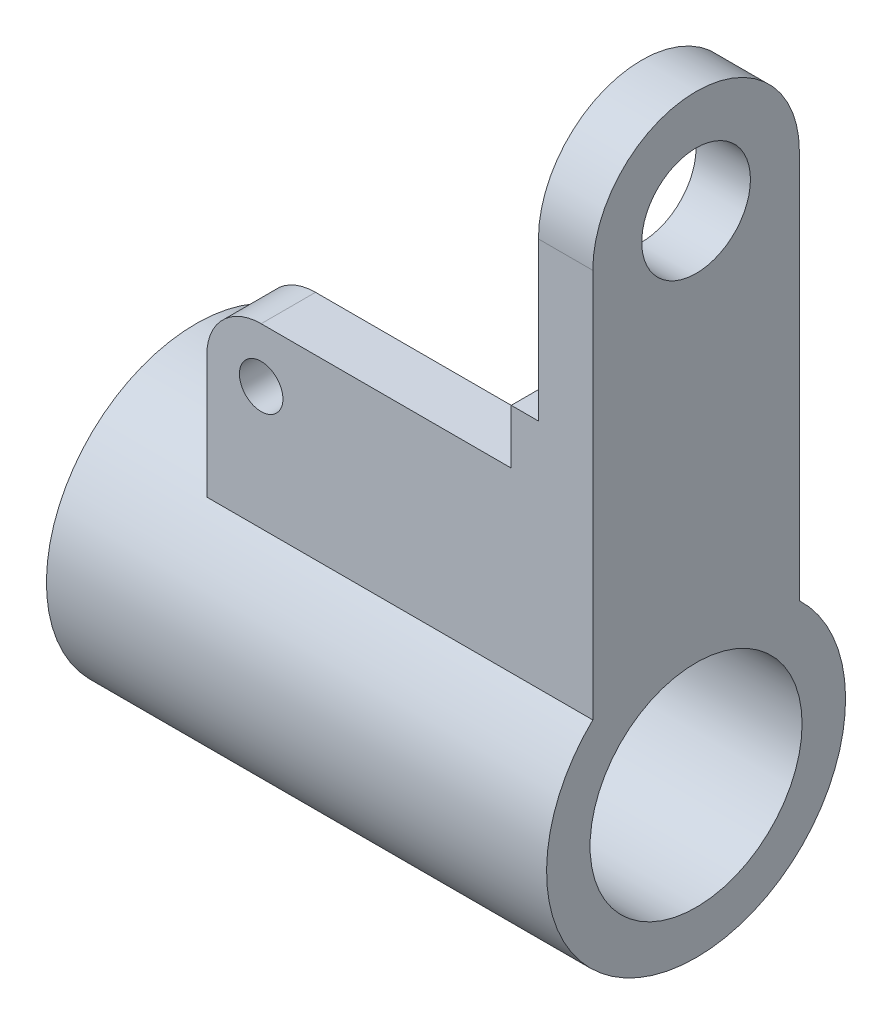
SolidWorks part; units mm, degrees
ref_plane "前视基准面" through (0, 0, 0) normal (0, 0, 1) x (1, 0, 0)
ref_plane "上视基准面" through (0, 0, 0) normal (0, 1, 0) x (1, 0, 0)
ref_plane "右视基准面" through (0, 0, 0) normal (1, 0, 0) x (0, 0, -1)
other "Configuration Table"
sketch "草图1" plane through (0, 0, 0) normal (1, 0, 0) x (0, 0, -1)
  circle A0 centre (0, 0) radius 27.5
  circle A1 centre (0, 0) radius 19.5
  dimension "D1" = 39
  dimension "D2" = 8
extrude "凸台-拉伸1" add sketch "草图1" along normal blind 92
sketch "草图2" plane through (92, 0, 0) normal (1, 0, 0) x (0, 0, -1)
  line L0 (-19, 19.8809) -> (-19, 91.5)
  line L1 (0, 0) -> (0, 96.1334) construction
  line L2 (19, 19.8809) -> (19, 91.5)
  circle A0 centre (0, 0) radius 27.5 construction
  arc A1 (19, 91.5) -> (-19, 91.5) centre (0, 91.5) ccw
  circle A2 centre (0, 91.5) radius 10
  arc A3 (19, 19.8809) -> (-19, 19.8809) centre (0, 0) ccw
  point P11 (0, -27.5)
  point P12 (0, 110.5)
  dimension "D1" = 38
  dimension "D3" = 20
  dimension "D2" = 138
extrude "凸台-拉伸2" add sketch "草图2" against normal blind 15
sketch "草图3" plane through (0, 0, 19) normal (0, 0, 1) x (1, 0, 0)
  line L0 (82, 110.5) -> (82, 62.5)
  line L1 (82, 62.5) -> (77, 62.5)
  line L2 (77, 62.5) -> (77, 110.5)
  line L3 (77, 110.5) -> (82, 110.5)
  line L4 (77, 91.5) -> (77, 19.8809) construction
  line L5 (92, 110.5) -> (77, 110.5) construction
  dimension "D1" = 5
  dimension "D2" = 48
extrude "切除-拉伸1" cut sketch "草图3" against normal up to next
sketch "草图6" plane through (77, 0, 0) normal (-1, 0, 0) x (0, 0, 1)
  line L0 (19, 19.8809) -> (19, 52.5)
  line L1 (19, 62.5) -> (19, 19.8809) construction
  line L2 (19, 52.5) -> (9, 52.5)
  line L3 (19, 19.8809) -> (19, 62.5)
  line L4 (19, 62.5) -> (-19, 62.5)
  line L5 (-19, 62.5) -> (-19, 19.8809)
  line L9 (9, 52.5) -> (9, 25.9856)
  line L10 (-19, 62.5) -> (19, 62.5) construction
  arc A1 (19, 19.8809) -> (-19, 19.8809) centre (0, 0) ccw
  arc A2 (19, 19.8809) -> (9, 25.9856) centre (0, 0) ccw
  dimension "D2" = 10
  dimension "D3" = 10
  dimension "D1" = 0
extrude "凸台-拉伸3" add sketch "草图6" along normal blind 56
fillet "圆角1" radius 10 1 edges at (21, 52.5, 14)
sketch "草图7" plane through (0, 0, 19) normal (0, 0, 1) x (1, 0, 0)
  circle A0 centre (31, 42.5) radius 4
  dimension "D1" = 8
extrude "切除-拉伸2" cut sketch "草图7" against normal up to next
